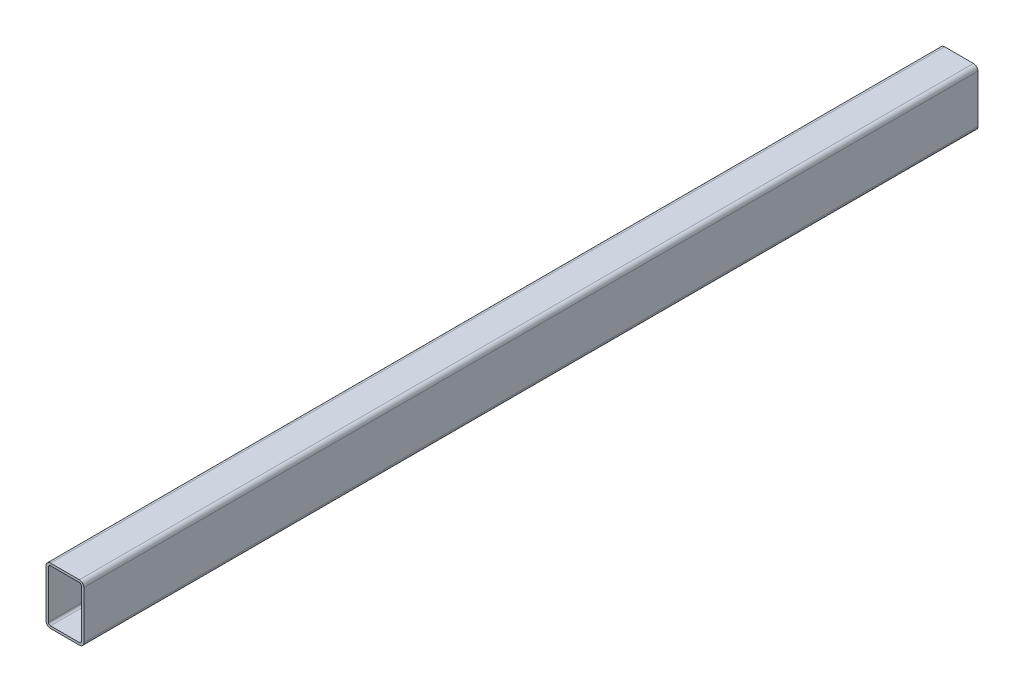
SolidWorks part; units mm, degrees
ref_plane "Front Plane" through (0, 0, 0) normal (0, 0, 1) x (1, 0, 0)
ref_plane "Top Plane" through (0, 0, 0) normal (0, 1, 0) x (1, 0, 0)
ref_plane "Right Plane" through (0, 0, 0) normal (1, 0, 0) x (0, 0, -1)
sketch "Sketch1" plane through (0, 0, 0) normal (0, 0, 1) x (1, 0, 0)
  line L0 (19.4, 34.925) -> (-19.4, 34.925)
  line L1 (19.4, -38.1) -> (-19.4, -38.1)
  line L2 (25.4, -32.1) -> (25.4, 32.1)
  line L3 (19.4, 38.1) -> (-19.4, 38.1)
  line L4 (-25.4, -32.1) -> (-25.4, 32.1)
  line L5 (25.4, -38.1) -> (-25.4, 38.1) construction
  line L6 (25.4, 38.1) -> (-25.4, -38.1) construction
  line L7 (-22.225, -32.1) -> (-22.225, 32.1)
  line L8 (19.4, -34.925) -> (-19.4, -34.925)
  line L9 (22.225, -32.1) -> (22.225, 32.1)
  arc A0 (-19.4, -38.1) -> (-25.4, -32.1) centre (-19.4, -32.1) cw
  arc A1 (19.4, -38.1) -> (25.4, -32.1) centre (19.4, -32.1) ccw
  arc A2 (25.4, 32.1) -> (19.4, 38.1) centre (19.4, 32.1) ccw
  arc A3 (-19.4, 38.1) -> (-25.4, 32.1) centre (-19.4, 32.1) ccw
  arc A4 (-19.4, 34.925) -> (-22.225, 32.1) centre (-19.4, 32.1) ccw
  arc A5 (-19.4, -34.925) -> (-22.225, -32.1) centre (-19.4, -32.1) cw
  arc A6 (19.4, -34.925) -> (22.225, -32.1) centre (19.4, -32.1) ccw
  arc A7 (22.225, 32.1) -> (19.4, 34.925) centre (19.4, 32.1) ccw
  point P0 (0, 0)
  dimension "D1" = 6
  dimension "D3" = 76.2
  dimension "D4" = 50.8
  dimension "D2" = 3.175
extrude "Boss-Extrude1" add sketch "Sketch1" along normal mid plane 1201.6
sketch "Sketch2" plane through (25.4, 0, 0) normal (1, 0, 0) x (0, 0, -1)
  line L0 (0, 197.5737) -> (0, -189.4858) construction
  line L1 (-600.8, -38.1) -> (600.8, -38.1) construction
  line L2 (-582.8, 20.1) -> (-568, 20.1) construction
  line L3 (-582.8, 20.1) -> (-582.8, -20.1) construction
  line L4 (-582.8, -20.1) -> (-568, -20.1) construction
  line L5 (-568, 20.1) -> (-568, -20.1) construction
  line L6 (-582.8, 20.1) -> (-568, -20.1) construction
  line L7 (-582.8, -20.1) -> (-568, 20.1) construction
  line L8 (-600.8, 38.1) -> (600.8, 38.1) construction
  line L9 (-582.8, 20.1) -> (-582.8, 38.1) construction
  line L10 (-582.8, 20.1) -> (-600.8, 20.1) construction
  line L11 (-600.8, -32.1) -> (-600.8, 32.1) construction
  line L12 (-600.8, 38.1) -> (-550, 38.1) construction
  line L13 (-600.8, 38.1) -> (-600.8, -38.1) construction
  line L14 (-600.8, -38.1) -> (-550, -38.1) construction
  line L15 (-550, 38.1) -> (-550, -38.1) construction
  line L16 (-575.4, -38.1) -> (-575.4, 38.1) construction
  line L17 (-600.8, 0) -> (-550, 0) construction
  circle A0 centre (-582.8, 20.1) radius 2.5
  circle A1 centre (-568, 20.1) radius 2.5
  circle A2 centre (-568, -20.1) radius 2.5
  circle A3 centre (-582.8, -20.1) radius 2.5
  circle A4 centre (-575.4, 0) radius 2.5
  circle A5 centre (568, -20.1) radius 2.5
  circle A6 centre (582.8, -20.1) radius 2.5
  circle A7 centre (575.4, 0) radius 2.5
  circle A8 centre (582.8, 20.1) radius 2.5
  circle A9 centre (568, 20.1) radius 2.5
  point P1 (-575.4, 0)
  dimension "D3" = 5
  dimension "D1" = 18
  dimension "D2" = 50.8
extrude "Cut-Extrude1" [suppressed] cut sketch "Sketch2" against normal through all
other "DeleteFace1" [suppressed]
equation "\"M5_tap\"=4.2mm\t\t\t\t\t\t\t' Below you can do mesurements as follows: cm, mm, ft, in, m, "
equation "\"M5_clearence\"=5.5mm"
equation "\"M6_tap\"=5mm"
equation "\"M6_clearence\"=6.6mm"
equation "\"work_area_width\"=1100mm"
equation "\"work_area_depth\"=900mm"
equation "\"D3@Sketch1\" = \"steel_base_width\""
equation "\"D4@Sketch1\" = \"steel_base_height\""
equation "\"D1@Sketch1\" = \"steel_base_radius\""
equation "\"D2@Sketch1\" = \"steel_base_wall_thickness\""
equation "\"D1@Boss-Extrude1\"=\"work_area_width\" + (\"steel_sides_height\"*2)"
equation "\"D1@Sketch2\" = \"steel_base_radius\" * 2 + 6mm"
equation "\"D2@Sketch2\"= \"steel_base_height\""
equation "\"D3@Sketch2\"=\"M6_tap\""
equation "\"steel_base_width\"=3in\t"
equation "\"steel_base_height\"=2in"
equation "\"steel_base_wall_thickness\"=0.125in"
equation "\"steel_base_radius\"=6mm"
equation "\"steel_sides_width\"=3in\t\t\t\t\t'this tube is rotated so flip width/height"
equation "\"steel_sides_height\"=2in\t\t\t\t'this tube is rotated so flip width/height"
equation "\"steel_sides_wall_thickness\"=0.125in"
equation "\"steel_sides_radius\"=6mm"
equation "\"steel_gantry_width\"=4in\t\t\t\t'this tube is rotated so flip width/height"
equation "\"steel_gantry_height\"=3in\t\t\t\t'this tube is rotated so flip width/height"
equation "\"steel_gantry_wall_thickness\"=0.125in"
equation "\"steel_gantry_radius\"=6mm"
